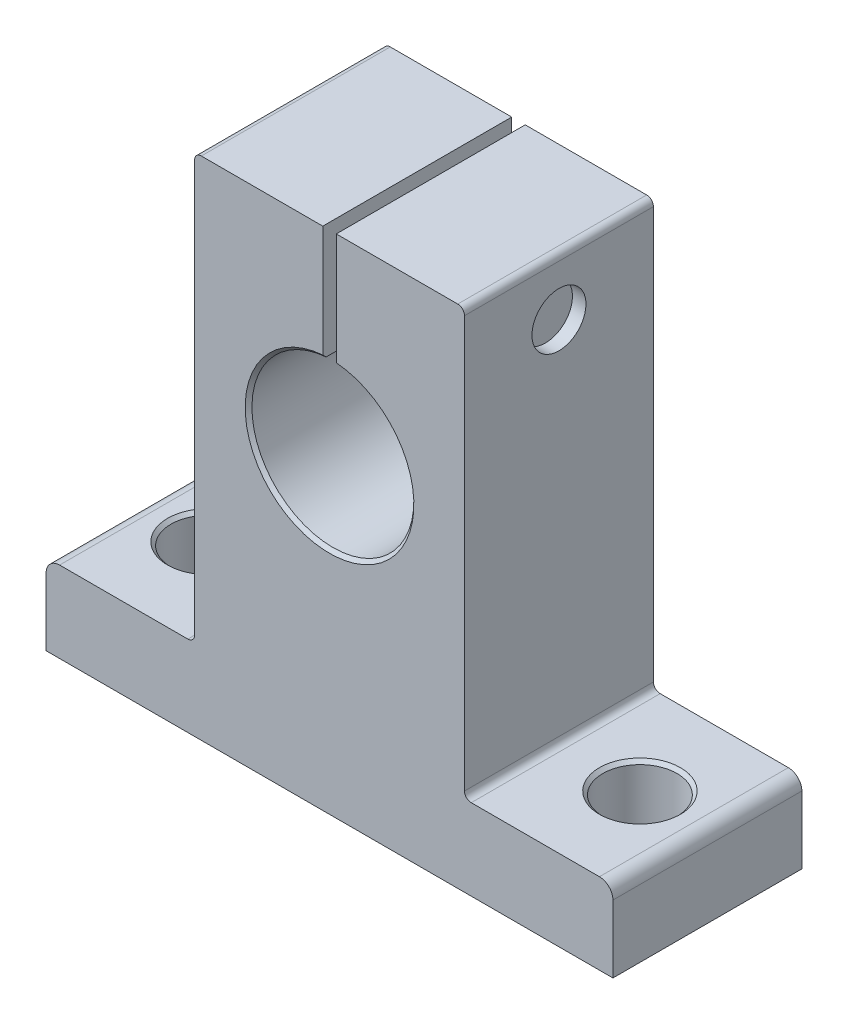
SolidWorks part; units mm, degrees
material "6061 Alloy"
ref_plane "Front Plane" through (0, 0, 0) normal (0, 0, 1) x (1, 0, 0)
ref_plane "Top Plane" through (0, 0, 0) normal (0, 1, 0) x (1, 0, 0)
ref_plane "Right Plane" through (0, 0, 0) normal (1, 0, 0) x (0, 0, -1)
sketch "Sketch1" plane through (0, 0, 0) normal (0, 0, 1) x (1, 0, 0)
  line L0 (-21, 0) -> (21, 0)
  line L1 (-21, 0) -> (-21, 6)
  line L2 (-21, 6) -> (-10, 6)
  line L3 (-10, 6) -> (-10, 37.5)
  line L4 (-10, 37.5) -> (-0.5, 37.5)
  line L5 (10, 37.5) -> (10, 6)
  line L6 (10, 6) -> (21, 6)
  line L7 (21, 6) -> (21, 0)
  line L8 (-0.5, 37.5) -> (-0.5, 28.9791)
  line L9 (0.5, 37.5) -> (0.5, 28.9791)
  line L10 (0.5, 37.5) -> (10, 37.5)
  arc A0 (-0.5, 28.9791) -> (0.5, 28.9791) centre (0, 23) ccw
  point P11 (0, 0)
  point P13 (-0.5, 33.2396)
  dimension "D6" = 6
  dimension "D1" = 42
  dimension "D2" = 6
  dimension "D3" = 23
  dimension "D4" = 37.5
  dimension "D5" = 1
  dimension "D7" = 20
extrude "Boss-Extrude1" add sketch "Sketch1" along normal blind 14
sketch "Sketch3" plane through (0, 0, 0) normal (0, -1, 0) x (1, 0, 0)
  line L0 (-16, 7) -> (16, 7) construction
  line L1 (-21, 14) -> (-21, 0) construction
  circle A0 centre (-16, 7) radius 2.75
  circle A1 centre (16, 7) radius 2.75
  point P2 (0, 7)
  point P7 (-21, 7)
  dimension "D2" = 5.5
  dimension "D1" = 32
extrude "Cut-Extrude1" cut sketch "Sketch3" against normal blind 6 and the other way through all
fillet "Fillet1" radius 1 2 edges at (21, 6, 7) (-21, 6, 7)
fillet "Fillet2" radius 0.5 4 edges at (-10, 37.5, 7) (10, 37.5, 7) (10, 6, 7) (-10, 6, 7)
chamfer "Chamfer1" distance 0.25 6 edges at (-16, 0, 9.75) (16, 0, 9.75) (18.75, 6, 7) (-13.25, 6, 7) (0, 17, 0) (0, 17, 14)
sketch "Sketch4" plane through (-10, 0, 0) normal (-1, 0, 0) x (0, 0, 1)
  line L0 (14, 37) -> (0, 37) construction
  line L1 (0, 37.5) -> (14, 37.5) construction
  circle A0 centre (7, 33.25) radius 3.1
  point P6 (7, 37)
  dimension "D1" = 6.2
  dimension "D2" = 4.25
extrude "Cut-Extrude2" cut sketch "Sketch4" against normal blind 1
sketch "Sketch5" plane through (-9, 0, 0) normal (-1, 0, 0) x (0, 0, 1)
  circle A0 centre (7, 33.25) radius 3.1
  circle A1 centre (7, 33.25) radius 3
  dimension "D1" = 6
  dimension "D2" = 6.2
extrude "Cut-Extrude3" cut sketch "Sketch5" against normal blind 4
chamfer "Chamfer2" distance 0.2 1 edges at (-9, 30.25, 7)
sketch "Sketch6" plane through (-9, 0, 0) normal (-1, 0, 0) x (0, 0, 1)
  line L1 (7.2461, 31.5355) -> (8.6078, 32.6059)
  line L2 (8.6078, 32.6059) -> (8.3618, 34.3203)
  line L3 (8.3618, 34.3203) -> (6.7539, 34.9645)
  line L4 (6.7539, 34.9645) -> (5.3922, 33.8941)
  line L5 (5.3922, 33.8941) -> (5.6382, 32.1797)
  line L6 (5.6382, 32.1797) -> (7.2461, 31.5355)
  circle A0 centre (7, 33.25) radius 1.5 construction
  dimension "D1" = 3
extrude "Cut-Extrude4" cut sketch "Sketch6" against normal blind 2
sketch "Sketch7" plane through (-0.5, 0, 0) normal (1, 0, 0) x (0, 0, -1)
  circle A0 centre (-7, 33.25) radius 2
  dimension "D1" = 4
extrude "Boss-Extrude2" add sketch "Sketch7" along normal blind 1
sketch "Sketch8" plane through (10, 0, 0) normal (1, 0, 0) x (0, 0, -1)
  circle A0 centre (-7, 33.25) radius 2
  dimension "D1" = 4
extrude "Cut-Extrude5" cut sketch "Sketch8" against normal blind 1
sketch "Sketch9" plane through (-9, 0, 0) normal (-1, 0, 0) x (0, 0, 1)
  circle A0 centre (7, 33.25) radius 1.7321
extrude "Cut-Extrude6" cut sketch "Sketch9" against normal blind 1 draft 45
equation "\"h\"= 23'6"
equation "\"w\"= 42'1"
equation "\"l\"= 14'3"
equation "\"f\"= 37.5'2"
equation "\"g\"= 6'9"
equation "\"p\"= 20'5"
equation "\"b\"= 32'4"
equation "\"s\"= 5.5'10"
equation "\"sk\"= 12'7 dg kinh truc"
equation "\"D1@Sketch1\"=\"w\""
equation "\"D2@Sketch1\"=\"g\""
equation "\"D3@Sketch1\"=\"h\""
equation "\"D4@Sketch1\"=\"f\""
equation "\"rk\"= 1'11 be rong khe"
equation "\"D5@Sketch1\"=\"rk\""
equation "\"D6@Sketch1\"=\"sk\"/2"
equation "\"D1@Boss-Extrude1\"=\"l\""
equation "\"D1@Sketch3\"=\"b\""
equation "\"D2@Sketch3\"=\"s\""
equation "\"D1@Cut-Extrude1\"=\"g\""
equation "\"D7@Sketch1\"=\"p\""
equation "\"bo\"= 1'12 bo goc"
equation "\"D1@Fillet1\"=\"bo\""
equation "\"D1@Fillet2\"=\"bo\"/2"
equation "\"D1@Chamfer1\"=\"bo\"/4"
equation "\"m\"= 4'8 bu long"
equation "\"D1@Sketch4\"=1.5*\"m\"+0.2"
equation "\"D1@Sketch5\"=\"m\"*1.5"
equation "\"D2@Sketch5\"=\"m\"*1.5+0.2"
equation "\"D1@Cut-Extrude3\"=\"m\""
equation "\"D1@Chamfer2\"=\"m\"*0.05"
equation "\"D1@Cut-Extrude4\"=\"m\"/2"
equation "\"D1@Sketch6\"=\"m\"*3/4"
equation "\"D1@Sketch7\"=\"m\""
equation "\"D1@Boss-Extrude2\"=\"rk\""
equation "\"D1@Sketch8\"=\"m\""
equation "\"D2@Sketch4\"=(\"f\"-\"h\"-\"sk\"/2)/2"
